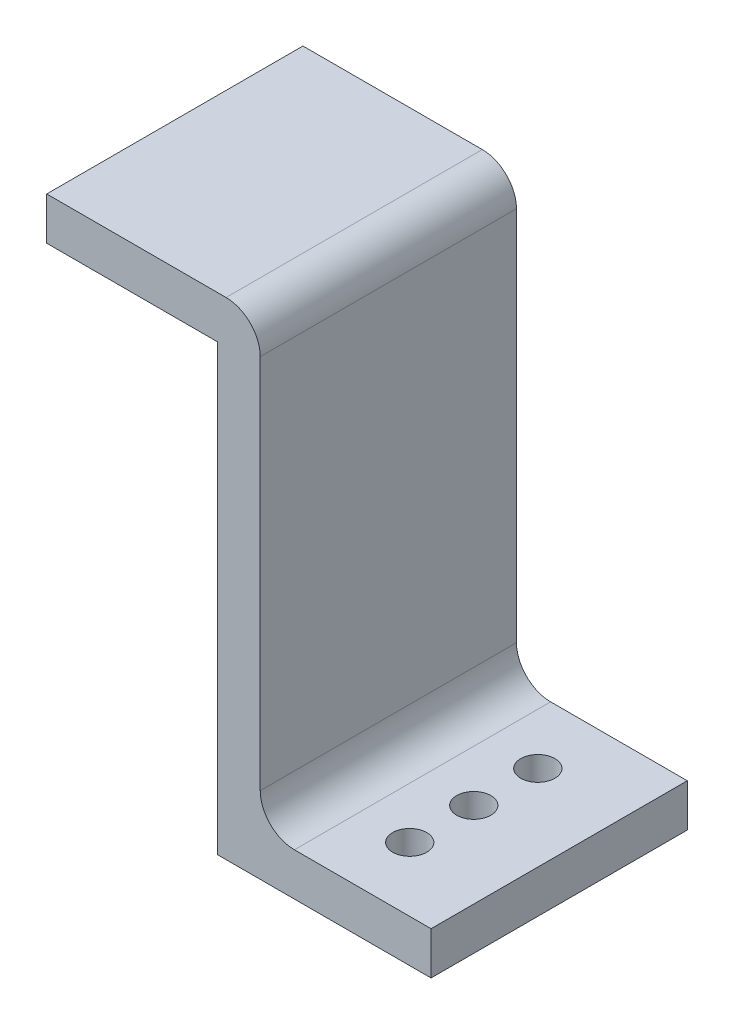
SolidWorks part; units mm, degrees
ref_plane "Front Plane" through (0, 0, 0) normal (0, 0, 1) x (1, 0, 0)
ref_plane "Top Plane" through (0, 0, 0) normal (0, 1, 0) x (1, 0, 0)
ref_plane "Right Plane" through (0, 0, 0) normal (1, 0, 0) x (0, 0, -1)
sketch "Sketch1" plane through (0, 0, 0) normal (0, 0, 1) x (1, 0, 0)
  line L1 (2.5, -28.5) -> (-2.5, -28.5)
  line L2 (2.5, -28.5) -> (2.5, 28.5)
  line L3 (2.5, 28.5) -> (-2.5, 28.5)
  line L4 (-2.5, -28.5) -> (-2.5, 28.5)
  line L5 (2.5, -28.5) -> (-2.5, 28.5) construction
  line L6 (2.5, 28.5) -> (-2.5, -28.5) construction
  line L7 (-2.5, 28.5) -> (-22.5, 28.5)
  line L8 (-2.5, 28.5) -> (-2.5, 23.5)
  line L9 (-2.5, 23.5) -> (-22.5, 23.5)
  line L10 (-22.5, 28.5) -> (-22.5, 23.5)
  line L11 (2.5, -28.5) -> (22.5, -28.5)
  line L12 (2.5, -28.5) -> (2.5, -23.5)
  line L13 (2.5, -23.5) -> (22.5, -23.5)
  line L14 (22.5, -28.5) -> (22.5, -23.5)
  point P0 (0, 0)
  dimension "D1" = 5
  dimension "D2" = 5
  dimension "D3" = 47
  dimension "D4" = 5
  dimension "D5" = 20
  dimension "D6" = 20
extrude "Boss-Extrude1" add sketch "Sketch1" along normal blind 30 contours L7 L10 L9 L4 | L4 L1 L2 L3 | L11 L14 L13 L12
fillet "Fillet1" radius 4 2 edges at (2.5, 28.5, 15) (2.5, -23.5, 15)
sketch "Sketch2" plane through (0, -23.5, 0) normal (0, 1, 0) x (1, 0, 0)
  line L0 (6.5, -30) -> (22.5, -30) construction
  line L1 (6.5, 0) -> (22.5, 0) construction
  line L2 (22.5, -30) -> (22.5, 0) construction
  circle A0 centre (12.5, -15) radius 2
  circle A1 centre (12.5, -22.5) radius 2
  circle A2 centre (12.5, -7.5) radius 2
  point P12 (0, 0)
  dimension "D1" = 4
  dimension "D2" = 4
  dimension "D3" = 7.5
  dimension "D4" = 7.5
  dimension "D5" = 7.5
  dimension "D6" = 4
  dimension "D7" = 7.5
  dimension "D8" = 10
extrude "Cut-Extrude1" cut sketch "Sketch2" against normal blind 30
